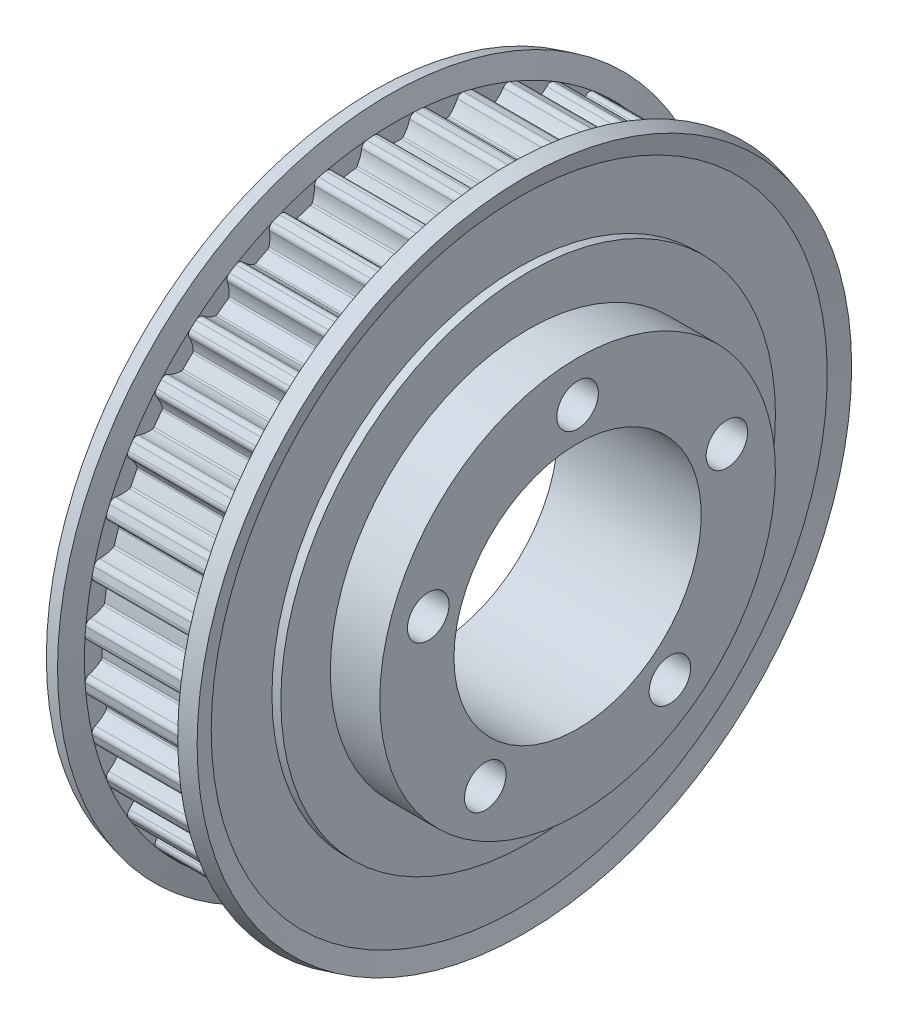
SolidWorks part; units mm, degrees
ref_plane "Front Plane" through (0, 0, 0) normal (0, 0, 1) x (1, 0, 0)
ref_plane "Top Plane" through (0, 0, 0) normal (0, 1, 0) x (1, 0, 0)
ref_plane "Right Plane" through (0, 0, 0) normal (1, 0, 0) x (0, 0, -1)
ref_plane "Plane1" through (0, 0, 0) normal (0, 0, 1) x (1, 0, 0)
sketch "Sketch1" plane through (0, 0, 0) normal (0, 0, 1) x (1, 0, 0)
  line L0 (0, 0) -> (0, 25)
  line L1 (0, 25) -> (0.9, 25)
  line L2 (0.9, 25) -> (0.9, 31.1394)
  line L3 (0.9, 31.1394) -> (0.3784, 33.0859)
  line L4 (0.3784, 33.0859) -> (1.9239, 33.5)
  line L5 (1.9239, 33.5) -> (2.5, 31.35)
  line L6 (2.5, 31.35) -> (13.5, 31.35)
  line L7 (13.5, 31.35) -> (14.0761, 33.5)
  line L8 (14.0761, 33.5) -> (15.6216, 33.0859)
  line L9 (15.6216, 33.0859) -> (15.1, 31.1394)
  line L10 (15.1, 31.1394) -> (15.1, 25)
  line L11 (15.1, 25) -> (16, 25)
  line L12 (16, 25) -> (16, 23.5)
  line L13 (16, 23.5) -> (21, 23.5)
  line L14 (21, 23.5) -> (21, 0)
  line L15 (21, 0) -> (0, 0)
  line L16 (21, 0) -> (0, 0) construction
revolve "Revolve1" add sketch "Sketch1" angle 360 about L16
ref_plane "Plane2" through (0, 0, 0) normal (0, 0, 1) x (1, 0, 0)
sketch "Sketch2" plane through (0, 0, 0) normal (0, 0, 1) x (1, 0, 0)
  line L0 (0, 0) -> (0, 12.5)
  line L1 (0, 12.5) -> (21, 12.5)
  line L2 (21, 12.5) -> (21, 0)
  line L3 (21, 0) -> (0, 0)
  line L4 (21, 0) -> (0, 0) construction
revolve "Cut-Revolve1" cut sketch "Sketch2" angle 360 about L4
ref_plane "Plane3" through (2.5, 0, 0) normal (1, 0, 0) x (0, 0, -1)
sketch "Sketch3" plane through (2.5, 0, 0) normal (1, 0, 0) x (0, 0, -1)
  line L0 (2.0877, 31.2804) -> (2.0877, 31.7615)
  line L1 (-2.0877, 31.7615) -> (-2.0877, 31.2804)
  arc A0 (-2.0877, 31.2804) -> (-1.5225, 30.8836) centre (-2.0511, 30.7316) cw
  arc A1 (-1.5225, 30.8836) -> (-0.8639, 29.6599) centre (1.625, 31.7885) ccw
  arc A2 (-0.8639, 29.6599) -> (-0.6683, 29.5725) centre (-0.6739, 29.8224) ccw
  arc A3 (-0.6683, 29.5725) -> (0.6683, 29.5725) centre (0, 0) cw
  arc A4 (0.6683, 29.5725) -> (0.8639, 29.6599) centre (0.6739, 29.8224) ccw
  arc A5 (0.8639, 29.6599) -> (1.5225, 30.8836) centre (-1.625, 31.7885) ccw
  arc A6 (1.5225, 30.8836) -> (2.0877, 31.2804) centre (2.0511, 30.7316) cw
  arc A7 (2.0877, 31.7615) -> (-2.0877, 31.7615) centre (0, 0) ccw
extrude "Cut-Extrude1" cut sketch "Sketch3" along normal blind 11
ref_plane "Plane4" through (2.5, 0, 0) normal (1, 0, 0) x (0, 0, -1)
sketch "Sketch4" plane through (2.5, 0, 0) normal (1, 0, 0) x (0, 0, -1)
  line L0 (6.9554, 30.5687) -> (7.0306, 31.0438)
  line L1 (2.9066, 31.697) -> (2.8313, 31.2219)
  arc A0 (2.8313, 31.2219) -> (3.3275, 30.7415) centre (2.7816, 30.6741) cw
  arc A1 (3.3275, 30.7415) -> (3.7865, 29.4299) centre (6.5778, 31.1429) ccw
  arc A2 (3.7865, 29.4299) -> (3.9661, 29.3129) centre (3.9996, 29.5606) ccw
  arc A3 (3.9661, 29.3129) -> (5.2862, 29.1038) centre (0, 0) cw
  arc A4 (5.2862, 29.1038) -> (5.4931, 29.1596) centre (5.3309, 29.3498) ccw
  arc A5 (5.4931, 29.1596) -> (6.335, 30.2652) centre (3.3678, 31.6513) ccw
  arc A6 (6.335, 30.2652) -> (6.9554, 30.5687) centre (6.8333, 30.0324) cw
  arc A7 (7.0306, 31.0438) -> (2.9066, 31.697) centre (0, 0) ccw
extrude "Cut-Extrude2" cut sketch "Sketch4" along normal blind 11
ref_plane "Plane5" through (2.5, 0, 0) normal (1, 0, 0) x (0, 0, -1)
sketch "Sketch5" plane through (2.5, 0, 0) normal (1, 0, 0) x (0, 0, -1)
  line L0 (11.6517, 29.1043) -> (11.8004, 29.5618)
  line L1 (7.8293, 30.8521) -> (7.6806, 30.3946)
  arc A0 (7.6806, 30.3946) -> (8.0956, 29.8425) centre (7.5459, 29.8613) cw
  arc A1 (8.0956, 29.8425) -> (8.3438, 28.4752) centre (11.3687, 29.7305) ccw
  arc A2 (8.3438, 28.4752) -> (8.5028, 28.3316) centre (8.5747, 28.571) ccw
  arc A3 (8.5028, 28.3316) -> (9.774, 27.9186) centre (0, 0) cw
  arc A4 (9.774, 27.9186) -> (9.987, 27.9413) centre (9.8566, 28.1545) ccw
  arc A5 (9.987, 27.9413) -> (10.9915, 28.9016) centre (8.2777, 30.7348) ccw
  arc A6 (10.9915, 28.9016) -> (11.6517, 29.1043) centre (11.4473, 28.5937) cw
  arc A7 (11.8004, 29.5618) -> (7.8293, 30.8521) centre (0, 0) ccw
extrude "Cut-Extrude3" cut sketch "Sketch5" along normal blind 11
ref_plane "Plane6" through (2.5, 0, 0) normal (1, 0, 0) x (0, 0, -1)
sketch "Sketch6" plane through (2.5, 0, 0) normal (1, 0, 0) x (0, 0, -1)
  line L0 (16.0612, 26.9232) -> (16.2796, 27.3519)
  line L1 (12.5592, 29.2475) -> (12.3408, 28.8189)
  arc A0 (12.3408, 28.8189) -> (12.6643, 28.2087) centre (12.1243, 28.3133) cw
  arc A1 (12.6643, 28.2087) -> (12.6956, 26.8194) centre (15.8796, 27.586) ccw
  arc A2 (12.6956, 26.8194) -> (12.8302, 26.6526) centre (12.9386, 26.8779) ccw
  arc A3 (12.8302, 26.6526) -> (14.021, 26.0459) centre (0, 0) cw
  arc A4 (14.021, 26.0459) -> (14.2351, 26.035) centre (14.1396, 26.266) ccw
  arc A5 (14.2351, 26.035) -> (15.3774, 26.8263) centre (12.9838, 29.0615) ccw
  arc A6 (15.3774, 26.8263) -> (16.0612, 26.9232) centre (15.7794, 26.4509) cw
  arc A7 (16.2796, 27.3519) -> (12.5592, 29.2475) centre (0, 0) ccw
extrude "Cut-Extrude4" cut sketch "Sketch6" along normal blind 11
ref_plane "Plane7" through (2.5, 0, 0) normal (1, 0, 0) x (0, 0, -1)
sketch "Sketch7" plane through (2.5, 0, 0) normal (1, 0, 0) x (0, 0, -1)
  line L0 (20.0752, 24.0793) -> (20.3579, 24.4684)
  line L1 (16.9799, 26.9227) -> (16.6972, 26.5335)
  arc A0 (16.6972, 26.5335) -> (16.9212, 25.8803) centre (16.4042, 26.068) cw
  arc A1 (16.9212, 25.8803) -> (16.7347, 24.5032) centre (19.9995, 24.7623) ccw
  arc A2 (16.7347, 24.5032) -> (16.8416, 24.3174) centre (16.9839, 24.5229) ccw
  arc A3 (16.8416, 24.3174) -> (17.9229, 23.5318) centre (0, 0) cw
  arc A4 (17.9229, 23.5318) -> (18.1326, 23.4876) centre (18.0744, 23.7307) ccw
  arc A5 (18.1326, 23.4876) -> (19.3847, 24.0904) centre (17.3702, 26.6726) ccw
  arc A6 (19.3847, 24.0904) -> (20.0752, 24.0793) centre (19.723, 23.6568) cw
  arc A7 (20.3579, 24.4684) -> (16.9799, 26.9227) centre (0, 0) ccw
extrude "Cut-Extrude5" cut sketch "Sketch7" along normal blind 11
ref_plane "Plane8" through (2.5, 0, 0) normal (1, 0, 0) x (0, 0, -1)
sketch "Sketch8" plane through (2.5, 0, 0) normal (1, 0, 0) x (0, 0, -1)
  line L0 (23.5948, 20.6423) -> (23.935, 20.9825)
  line L1 (20.9825, 23.935) -> (20.6423, 23.5948)
  arc A0 (20.6423, 23.5948) -> (20.7614, 22.9146) centre (20.2802, 23.1809) cw
  arc A1 (20.7614, 22.9146) -> (20.3618, 21.5836) centre (23.6269, 21.3288) ccw
  arc A2 (20.3618, 21.5836) -> (20.4383, 21.3834) centre (20.6111, 21.5641) ccw
  arc A3 (20.4383, 21.3834) -> (21.3834, 20.4383) centre (0, 0) cw
  arc A4 (21.3834, 20.4383) -> (21.5836, 20.3618) centre (21.5641, 20.6111) ccw
  arc A5 (21.5836, 20.3618) -> (22.9146, 20.7614) centre (21.3288, 23.6269) ccw
  arc A6 (22.9146, 20.7614) -> (23.5948, 20.6423) centre (23.1809, 20.2802) cw
  arc A7 (23.935, 20.9825) -> (20.9825, 23.935) centre (0, 0) ccw
extrude "Cut-Extrude6" cut sketch "Sketch8" along normal blind 11
ref_plane "Plane9" through (2.5, 0, 0) normal (1, 0, 0) x (0, 0, -1)
sketch "Sketch9" plane through (2.5, 0, 0) normal (1, 0, 0) x (0, 0, -1)
  line L0 (26.5335, 16.6972) -> (26.9227, 16.9799)
  line L1 (24.4684, 20.3579) -> (24.0793, 20.0752)
  arc A0 (24.0793, 20.0752) -> (24.0904, 19.3847) centre (23.6568, 19.723) cw
  arc A1 (24.0904, 19.3847) -> (23.4876, 18.1326) centre (26.6726, 17.3702) ccw
  arc A2 (23.4876, 18.1326) -> (23.5318, 17.9229) centre (23.7307, 18.0744) ccw
  arc A3 (23.5318, 17.9229) -> (24.3174, 16.8416) centre (0, 0) cw
  arc A4 (24.3174, 16.8416) -> (24.5032, 16.7347) centre (24.5229, 16.9839) ccw
  arc A5 (24.5032, 16.7347) -> (25.8803, 16.9212) centre (24.7623, 19.9995) ccw
  arc A6 (25.8803, 16.9212) -> (26.5335, 16.6972) centre (26.068, 16.4042) cw
  arc A7 (26.9227, 16.9799) -> (24.4684, 20.3579) centre (0, 0) ccw
extrude "Cut-Extrude7" cut sketch "Sketch9" along normal blind 11
ref_plane "Plane10" through (2.5, 0, 0) normal (1, 0, 0) x (0, 0, -1)
sketch "Sketch10" plane through (2.5, 0, 0) normal (1, 0, 0) x (0, 0, -1)
  line L0 (28.8189, 12.3408) -> (29.2475, 12.5592)
  line L1 (27.3519, 16.2796) -> (26.9232, 16.0612)
  arc A0 (26.9232, 16.0612) -> (26.8263, 15.3774) centre (26.4509, 15.7794) cw
  arc A1 (26.8263, 15.3774) -> (26.035, 14.2351) centre (29.0615, 12.9838) ccw
  arc A2 (26.035, 14.2351) -> (26.0459, 14.021) centre (26.266, 14.1396) ccw
  arc A3 (26.0459, 14.021) -> (26.6526, 12.8302) centre (0, 0) cw
  arc A4 (26.6526, 12.8302) -> (26.8194, 12.6956) centre (26.8779, 12.9386) ccw
  arc A5 (26.8194, 12.6956) -> (28.2087, 12.6643) centre (27.586, 15.8796) ccw
  arc A6 (28.2087, 12.6643) -> (28.8189, 12.3408) centre (28.3133, 12.1243) cw
  arc A7 (29.2475, 12.5592) -> (27.3519, 16.2796) centre (0, 0) ccw
extrude "Cut-Extrude8" cut sketch "Sketch10" along normal blind 11
ref_plane "Plane11" through (2.5, 0, 0) normal (1, 0, 0) x (0, 0, -1)
sketch "Sketch11" plane through (2.5, 0, 0) normal (1, 0, 0) x (0, 0, -1)
  line L0 (30.3946, 7.6806) -> (30.8521, 7.8293)
  line L1 (29.5618, 11.8004) -> (29.1043, 11.6517)
  arc A0 (29.1043, 11.6517) -> (28.9016, 10.9915) centre (28.5937, 11.4473) cw
  arc A1 (28.9016, 10.9915) -> (27.9413, 9.987) centre (30.7348, 8.2777) ccw
  arc A2 (27.9413, 9.987) -> (27.9186, 9.774) centre (28.1545, 9.8566) ccw
  arc A3 (27.9186, 9.774) -> (28.3316, 8.5028) centre (0, 0) cw
  arc A4 (28.3316, 8.5028) -> (28.4752, 8.3438) centre (28.571, 8.5747) ccw
  arc A5 (28.4752, 8.3438) -> (29.8425, 8.0956) centre (29.7305, 11.3687) ccw
  arc A6 (29.8425, 8.0956) -> (30.3946, 7.6806) centre (29.8613, 7.5459) cw
  arc A7 (30.8521, 7.8293) -> (29.5618, 11.8004) centre (0, 0) ccw
extrude "Cut-Extrude9" cut sketch "Sketch11" along normal blind 11
ref_plane "Plane12" through (2.5, 0, 0) normal (1, 0, 0) x (0, 0, -1)
sketch "Sketch12" plane through (2.5, 0, 0) normal (1, 0, 0) x (0, 0, -1)
  line L0 (31.2219, 2.8313) -> (31.697, 2.9066)
  line L1 (31.0438, 7.0306) -> (30.5687, 6.9554)
  arc A0 (30.5687, 6.9554) -> (30.2652, 6.335) centre (30.0324, 6.8333) cw
  arc A1 (30.2652, 6.335) -> (29.1596, 5.4931) centre (31.6513, 3.3678) ccw
  arc A2 (29.1596, 5.4931) -> (29.1038, 5.2862) centre (29.3498, 5.3309) ccw
  arc A3 (29.1038, 5.2862) -> (29.3129, 3.9661) centre (0, 0) cw
  arc A4 (29.3129, 3.9661) -> (29.4299, 3.7865) centre (29.5606, 3.9996) ccw
  arc A5 (29.4299, 3.7865) -> (30.7415, 3.3275) centre (31.1429, 6.5778) ccw
  arc A6 (30.7415, 3.3275) -> (31.2219, 2.8313) centre (30.6741, 2.7816) cw
  arc A7 (31.697, 2.9066) -> (31.0438, 7.0306) centre (0, 0) ccw
extrude "Cut-Extrude10" cut sketch "Sketch12" along normal blind 11
ref_plane "Plane13" through (2.5, 0, 0) normal (1, 0, 0) x (0, 0, -1)
sketch "Sketch13" plane through (2.5, 0, 0) normal (1, 0, 0) x (0, 0, -1)
  line L0 (31.2804, -2.0877) -> (31.7615, -2.0877)
  line L1 (31.7615, 2.0877) -> (31.2804, 2.0877)
  arc A0 (31.2804, 2.0877) -> (30.8836, 1.5225) centre (30.7316, 2.0511) cw
  arc A1 (30.8836, 1.5225) -> (29.6599, 0.8639) centre (31.7885, -1.625) ccw
  arc A2 (29.6599, 0.8639) -> (29.5725, 0.6683) centre (29.8224, 0.6739) ccw
  arc A3 (29.5725, 0.6683) -> (29.5725, -0.6683) centre (0, 0) cw
  arc A4 (29.5725, -0.6683) -> (29.6599, -0.8639) centre (29.8224, -0.6739) ccw
  arc A5 (29.6599, -0.8639) -> (30.8836, -1.5225) centre (31.7885, 1.625) ccw
  arc A6 (30.8836, -1.5225) -> (31.2804, -2.0877) centre (30.7316, -2.0511) cw
  arc A7 (31.7615, -2.0877) -> (31.7615, 2.0877) centre (0, 0) ccw
extrude "Cut-Extrude11" cut sketch "Sketch13" along normal blind 11
ref_plane "Plane14" through (2.5, 0, 0) normal (1, 0, 0) x (0, 0, -1)
sketch "Sketch14" plane through (2.5, 0, 0) normal (1, 0, 0) x (0, 0, -1)
  line L0 (30.5687, -6.9554) -> (31.0438, -7.0306)
  line L1 (31.697, -2.9066) -> (31.2219, -2.8313)
  arc A0 (31.2219, -2.8313) -> (30.7415, -3.3275) centre (30.6741, -2.7816) cw
  arc A1 (30.7415, -3.3275) -> (29.4299, -3.7865) centre (31.1429, -6.5778) ccw
  arc A2 (29.4299, -3.7865) -> (29.3129, -3.9661) centre (29.5606, -3.9996) ccw
  arc A3 (29.3129, -3.9661) -> (29.1038, -5.2862) centre (0, 0) cw
  arc A4 (29.1038, -5.2862) -> (29.1596, -5.4931) centre (29.3498, -5.3309) ccw
  arc A5 (29.1596, -5.4931) -> (30.2652, -6.335) centre (31.6513, -3.3678) ccw
  arc A6 (30.2652, -6.335) -> (30.5687, -6.9554) centre (30.0324, -6.8333) cw
  arc A7 (31.0438, -7.0306) -> (31.697, -2.9066) centre (0, 0) ccw
extrude "Cut-Extrude12" cut sketch "Sketch14" along normal blind 11
ref_plane "Plane15" through (2.5, 0, 0) normal (1, 0, 0) x (0, 0, -1)
sketch "Sketch15" plane through (2.5, 0, 0) normal (1, 0, 0) x (0, 0, -1)
  line L0 (29.1043, -11.6517) -> (29.5618, -11.8004)
  line L1 (30.8521, -7.8293) -> (30.3946, -7.6806)
  arc A0 (30.3946, -7.6806) -> (29.8425, -8.0956) centre (29.8613, -7.5459) cw
  arc A1 (29.8425, -8.0956) -> (28.4752, -8.3438) centre (29.7305, -11.3687) ccw
  arc A2 (28.4752, -8.3438) -> (28.3316, -8.5028) centre (28.571, -8.5747) ccw
  arc A3 (28.3316, -8.5028) -> (27.9186, -9.774) centre (0, 0) cw
  arc A4 (27.9186, -9.774) -> (27.9413, -9.987) centre (28.1545, -9.8566) ccw
  arc A5 (27.9413, -9.987) -> (28.9016, -10.9915) centre (30.7348, -8.2777) ccw
  arc A6 (28.9016, -10.9915) -> (29.1043, -11.6517) centre (28.5937, -11.4473) cw
  arc A7 (29.5618, -11.8004) -> (30.8521, -7.8293) centre (0, 0) ccw
extrude "Cut-Extrude13" cut sketch "Sketch15" along normal blind 11
ref_plane "Plane16" through (2.5, 0, 0) normal (1, 0, 0) x (0, 0, -1)
sketch "Sketch16" plane through (2.5, 0, 0) normal (1, 0, 0) x (0, 0, -1)
  line L0 (26.9232, -16.0612) -> (27.3519, -16.2796)
  line L1 (29.2475, -12.5592) -> (28.8189, -12.3408)
  arc A0 (28.8189, -12.3408) -> (28.2087, -12.6643) centre (28.3133, -12.1243) cw
  arc A1 (28.2087, -12.6643) -> (26.8194, -12.6956) centre (27.586, -15.8796) ccw
  arc A2 (26.8194, -12.6956) -> (26.6526, -12.8302) centre (26.8779, -12.9386) ccw
  arc A3 (26.6526, -12.8302) -> (26.0459, -14.021) centre (0, 0) cw
  arc A4 (26.0459, -14.021) -> (26.035, -14.2351) centre (26.266, -14.1396) ccw
  arc A5 (26.035, -14.2351) -> (26.8263, -15.3774) centre (29.0615, -12.9838) ccw
  arc A6 (26.8263, -15.3774) -> (26.9232, -16.0612) centre (26.4509, -15.7794) cw
  arc A7 (27.3519, -16.2796) -> (29.2475, -12.5592) centre (0, 0) ccw
extrude "Cut-Extrude14" cut sketch "Sketch16" along normal blind 11
ref_plane "Plane17" through (2.5, 0, 0) normal (1, 0, 0) x (0, 0, -1)
sketch "Sketch17" plane through (2.5, 0, 0) normal (1, 0, 0) x (0, 0, -1)
  line L0 (24.0793, -20.0752) -> (24.4684, -20.3579)
  line L1 (26.9227, -16.9799) -> (26.5335, -16.6972)
  arc A0 (26.5335, -16.6972) -> (25.8803, -16.9212) centre (26.068, -16.4042) cw
  arc A1 (25.8803, -16.9212) -> (24.5032, -16.7347) centre (24.7623, -19.9995) ccw
  arc A2 (24.5032, -16.7347) -> (24.3174, -16.8416) centre (24.5229, -16.9839) ccw
  arc A3 (24.3174, -16.8416) -> (23.5318, -17.9229) centre (0, 0) cw
  arc A4 (23.5318, -17.9229) -> (23.4876, -18.1326) centre (23.7307, -18.0744) ccw
  arc A5 (23.4876, -18.1326) -> (24.0904, -19.3847) centre (26.6726, -17.3702) ccw
  arc A6 (24.0904, -19.3847) -> (24.0793, -20.0752) centre (23.6568, -19.723) cw
  arc A7 (24.4684, -20.3579) -> (26.9227, -16.9799) centre (0, 0) ccw
extrude "Cut-Extrude15" cut sketch "Sketch17" along normal blind 11
ref_plane "Plane18" through (2.5, 0, 0) normal (1, 0, 0) x (0, 0, -1)
sketch "Sketch18" plane through (2.5, 0, 0) normal (1, 0, 0) x (0, 0, -1)
  line L0 (20.6423, -23.5948) -> (20.9825, -23.935)
  line L1 (23.935, -20.9825) -> (23.5948, -20.6423)
  arc A0 (23.5948, -20.6423) -> (22.9146, -20.7614) centre (23.1809, -20.2802) cw
  arc A1 (22.9146, -20.7614) -> (21.5836, -20.3618) centre (21.3288, -23.6269) ccw
  arc A2 (21.5836, -20.3618) -> (21.3834, -20.4383) centre (21.5641, -20.6111) ccw
  arc A3 (21.3834, -20.4383) -> (20.4383, -21.3834) centre (0, 0) cw
  arc A4 (20.4383, -21.3834) -> (20.3618, -21.5836) centre (20.6111, -21.5641) ccw
  arc A5 (20.3618, -21.5836) -> (20.7614, -22.9146) centre (23.6269, -21.3288) ccw
  arc A6 (20.7614, -22.9146) -> (20.6423, -23.5948) centre (20.2802, -23.1809) cw
  arc A7 (20.9825, -23.935) -> (23.935, -20.9825) centre (0, 0) ccw
extrude "Cut-Extrude16" cut sketch "Sketch18" along normal blind 11
ref_plane "Plane19" through (2.5, 0, 0) normal (1, 0, 0) x (0, 0, -1)
sketch "Sketch19" plane through (2.5, 0, 0) normal (1, 0, 0) x (0, 0, -1)
  line L0 (16.6972, -26.5335) -> (16.9799, -26.9227)
  line L1 (20.3579, -24.4684) -> (20.0752, -24.0793)
  arc A0 (20.0752, -24.0793) -> (19.3847, -24.0904) centre (19.723, -23.6568) cw
  arc A1 (19.3847, -24.0904) -> (18.1326, -23.4876) centre (17.3702, -26.6726) ccw
  arc A2 (18.1326, -23.4876) -> (17.9229, -23.5318) centre (18.0744, -23.7307) ccw
  arc A3 (17.9229, -23.5318) -> (16.8416, -24.3174) centre (0, 0) cw
  arc A4 (16.8416, -24.3174) -> (16.7347, -24.5032) centre (16.9839, -24.5229) ccw
  arc A5 (16.7347, -24.5032) -> (16.9212, -25.8803) centre (19.9995, -24.7623) ccw
  arc A6 (16.9212, -25.8803) -> (16.6972, -26.5335) centre (16.4042, -26.068) cw
  arc A7 (16.9799, -26.9227) -> (20.3579, -24.4684) centre (0, 0) ccw
extrude "Cut-Extrude17" cut sketch "Sketch19" along normal blind 11
ref_plane "Plane20" through (2.5, 0, 0) normal (1, 0, 0) x (0, 0, -1)
sketch "Sketch20" plane through (2.5, 0, 0) normal (1, 0, 0) x (0, 0, -1)
  line L0 (12.3408, -28.8189) -> (12.5592, -29.2475)
  line L1 (16.2796, -27.3519) -> (16.0612, -26.9232)
  arc A0 (16.0612, -26.9232) -> (15.3774, -26.8263) centre (15.7794, -26.4509) cw
  arc A1 (15.3774, -26.8263) -> (14.2351, -26.035) centre (12.9838, -29.0615) ccw
  arc A2 (14.2351, -26.035) -> (14.021, -26.0459) centre (14.1396, -26.266) ccw
  arc A3 (14.021, -26.0459) -> (12.8302, -26.6526) centre (0, 0) cw
  arc A4 (12.8302, -26.6526) -> (12.6956, -26.8194) centre (12.9386, -26.8779) ccw
  arc A5 (12.6956, -26.8194) -> (12.6643, -28.2087) centre (15.8796, -27.586) ccw
  arc A6 (12.6643, -28.2087) -> (12.3408, -28.8189) centre (12.1243, -28.3133) cw
  arc A7 (12.5592, -29.2475) -> (16.2796, -27.3519) centre (0, 0) ccw
extrude "Cut-Extrude18" cut sketch "Sketch20" along normal blind 11
ref_plane "Plane21" through (2.5, 0, 0) normal (1, 0, 0) x (0, 0, -1)
sketch "Sketch21" plane through (2.5, 0, 0) normal (1, 0, 0) x (0, 0, -1)
  line L0 (7.6806, -30.3946) -> (7.8293, -30.8521)
  line L1 (11.8004, -29.5618) -> (11.6517, -29.1043)
  arc A0 (11.6517, -29.1043) -> (10.9915, -28.9016) centre (11.4473, -28.5937) cw
  arc A1 (10.9915, -28.9016) -> (9.987, -27.9413) centre (8.2777, -30.7348) ccw
  arc A2 (9.987, -27.9413) -> (9.774, -27.9186) centre (9.8566, -28.1545) ccw
  arc A3 (9.774, -27.9186) -> (8.5028, -28.3316) centre (0, 0) cw
  arc A4 (8.5028, -28.3316) -> (8.3438, -28.4752) centre (8.5747, -28.571) ccw
  arc A5 (8.3438, -28.4752) -> (8.0956, -29.8425) centre (11.3687, -29.7305) ccw
  arc A6 (8.0956, -29.8425) -> (7.6806, -30.3946) centre (7.5459, -29.8613) cw
  arc A7 (7.8293, -30.8521) -> (11.8004, -29.5618) centre (0, 0) ccw
extrude "Cut-Extrude19" cut sketch "Sketch21" along normal blind 11
ref_plane "Plane22" through (2.5, 0, 0) normal (1, 0, 0) x (0, 0, -1)
sketch "Sketch22" plane through (2.5, 0, 0) normal (1, 0, 0) x (0, 0, -1)
  line L0 (2.8313, -31.2219) -> (2.9066, -31.697)
  line L1 (7.0306, -31.0438) -> (6.9554, -30.5687)
  arc A0 (6.9554, -30.5687) -> (6.335, -30.2652) centre (6.8333, -30.0324) cw
  arc A1 (6.335, -30.2652) -> (5.4931, -29.1596) centre (3.3678, -31.6513) ccw
  arc A2 (5.4931, -29.1596) -> (5.2862, -29.1038) centre (5.3309, -29.3498) ccw
  arc A3 (5.2862, -29.1038) -> (3.9661, -29.3129) centre (0, 0) cw
  arc A4 (3.9661, -29.3129) -> (3.7865, -29.4299) centre (3.9996, -29.5606) ccw
  arc A5 (3.7865, -29.4299) -> (3.3275, -30.7415) centre (6.5778, -31.1429) ccw
  arc A6 (3.3275, -30.7415) -> (2.8313, -31.2219) centre (2.7816, -30.6741) cw
  arc A7 (2.9066, -31.697) -> (7.0306, -31.0438) centre (0, 0) ccw
extrude "Cut-Extrude20" cut sketch "Sketch22" along normal blind 11
ref_plane "Plane23" through (2.5, 0, 0) normal (1, 0, 0) x (0, 0, -1)
sketch "Sketch23" plane through (2.5, 0, 0) normal (1, 0, 0) x (0, 0, -1)
  line L0 (-2.0877, -31.2804) -> (-2.0877, -31.7615)
  line L1 (2.0877, -31.7615) -> (2.0877, -31.2804)
  arc A0 (2.0877, -31.2804) -> (1.5225, -30.8836) centre (2.0511, -30.7316) cw
  arc A1 (1.5225, -30.8836) -> (0.8639, -29.6599) centre (-1.625, -31.7885) ccw
  arc A2 (0.8639, -29.6599) -> (0.6683, -29.5725) centre (0.6739, -29.8224) ccw
  arc A3 (0.6683, -29.5725) -> (-0.6683, -29.5725) centre (0, 0) cw
  arc A4 (-0.6683, -29.5725) -> (-0.8639, -29.6599) centre (-0.6739, -29.8224) ccw
  arc A5 (-0.8639, -29.6599) -> (-1.5225, -30.8836) centre (1.625, -31.7885) ccw
  arc A6 (-1.5225, -30.8836) -> (-2.0877, -31.2804) centre (-2.0511, -30.7316) cw
  arc A7 (-2.0877, -31.7615) -> (2.0877, -31.7615) centre (0, 0) ccw
extrude "Cut-Extrude21" cut sketch "Sketch23" along normal blind 11
ref_plane "Plane24" through (2.5, 0, 0) normal (1, 0, 0) x (0, 0, -1)
sketch "Sketch24" plane through (2.5, 0, 0) normal (1, 0, 0) x (0, 0, -1)
  line L0 (-6.9554, -30.5687) -> (-7.0306, -31.0438)
  line L1 (-2.9066, -31.697) -> (-2.8313, -31.2219)
  arc A0 (-2.8313, -31.2219) -> (-3.3275, -30.7415) centre (-2.7816, -30.6741) cw
  arc A1 (-3.3275, -30.7415) -> (-3.7865, -29.4299) centre (-6.5778, -31.1429) ccw
  arc A2 (-3.7865, -29.4299) -> (-3.9661, -29.3129) centre (-3.9996, -29.5606) ccw
  arc A3 (-3.9661, -29.3129) -> (-5.2862, -29.1038) centre (0, 0) cw
  arc A4 (-5.2862, -29.1038) -> (-5.4931, -29.1596) centre (-5.3309, -29.3498) ccw
  arc A5 (-5.4931, -29.1596) -> (-6.335, -30.2652) centre (-3.3678, -31.6513) ccw
  arc A6 (-6.335, -30.2652) -> (-6.9554, -30.5687) centre (-6.8333, -30.0324) cw
  arc A7 (-7.0306, -31.0438) -> (-2.9066, -31.697) centre (0, 0) ccw
extrude "Cut-Extrude22" cut sketch "Sketch24" along normal blind 11
ref_plane "Plane25" through (2.5, 0, 0) normal (1, 0, 0) x (0, 0, -1)
sketch "Sketch25" plane through (2.5, 0, 0) normal (1, 0, 0) x (0, 0, -1)
  line L0 (-11.6517, -29.1043) -> (-11.8004, -29.5618)
  line L1 (-7.8293, -30.8521) -> (-7.6806, -30.3946)
  arc A0 (-7.6806, -30.3946) -> (-8.0956, -29.8425) centre (-7.5459, -29.8613) cw
  arc A1 (-8.0956, -29.8425) -> (-8.3438, -28.4752) centre (-11.3687, -29.7305) ccw
  arc A2 (-8.3438, -28.4752) -> (-8.5028, -28.3316) centre (-8.5747, -28.571) ccw
  arc A3 (-8.5028, -28.3316) -> (-9.774, -27.9186) centre (0, 0) cw
  arc A4 (-9.774, -27.9186) -> (-9.987, -27.9413) centre (-9.8566, -28.1545) ccw
  arc A5 (-9.987, -27.9413) -> (-10.9915, -28.9016) centre (-8.2777, -30.7348) ccw
  arc A6 (-10.9915, -28.9016) -> (-11.6517, -29.1043) centre (-11.4473, -28.5937) cw
  arc A7 (-11.8004, -29.5618) -> (-7.8293, -30.8521) centre (0, 0) ccw
extrude "Cut-Extrude23" cut sketch "Sketch25" along normal blind 11
ref_plane "Plane26" through (2.5, 0, 0) normal (1, 0, 0) x (0, 0, -1)
sketch "Sketch26" plane through (2.5, 0, 0) normal (1, 0, 0) x (0, 0, -1)
  line L0 (-16.0612, -26.9232) -> (-16.2796, -27.3519)
  line L1 (-12.5592, -29.2475) -> (-12.3408, -28.8189)
  arc A0 (-12.3408, -28.8189) -> (-12.6643, -28.2087) centre (-12.1243, -28.3133) cw
  arc A1 (-12.6643, -28.2087) -> (-12.6956, -26.8194) centre (-15.8796, -27.586) ccw
  arc A2 (-12.6956, -26.8194) -> (-12.8302, -26.6526) centre (-12.9386, -26.8779) ccw
  arc A3 (-12.8302, -26.6526) -> (-14.021, -26.0459) centre (0, 0) cw
  arc A4 (-14.021, -26.0459) -> (-14.2351, -26.035) centre (-14.1396, -26.266) ccw
  arc A5 (-14.2351, -26.035) -> (-15.3774, -26.8263) centre (-12.9838, -29.0615) ccw
  arc A6 (-15.3774, -26.8263) -> (-16.0612, -26.9232) centre (-15.7794, -26.4509) cw
  arc A7 (-16.2796, -27.3519) -> (-12.5592, -29.2475) centre (0, 0) ccw
extrude "Cut-Extrude24" cut sketch "Sketch26" along normal blind 11
ref_plane "Plane27" through (2.5, 0, 0) normal (1, 0, 0) x (0, 0, -1)
sketch "Sketch27" plane through (2.5, 0, 0) normal (1, 0, 0) x (0, 0, -1)
  line L0 (-20.0752, -24.0793) -> (-20.3579, -24.4684)
  line L1 (-16.9799, -26.9227) -> (-16.6972, -26.5335)
  arc A0 (-16.6972, -26.5335) -> (-16.9212, -25.8803) centre (-16.4042, -26.068) cw
  arc A1 (-16.9212, -25.8803) -> (-16.7347, -24.5032) centre (-19.9995, -24.7623) ccw
  arc A2 (-16.7347, -24.5032) -> (-16.8416, -24.3174) centre (-16.9839, -24.5229) ccw
  arc A3 (-16.8416, -24.3174) -> (-17.9229, -23.5318) centre (0, 0) cw
  arc A4 (-17.9229, -23.5318) -> (-18.1326, -23.4876) centre (-18.0744, -23.7307) ccw
  arc A5 (-18.1326, -23.4876) -> (-19.3847, -24.0904) centre (-17.3702, -26.6726) ccw
  arc A6 (-19.3847, -24.0904) -> (-20.0752, -24.0793) centre (-19.723, -23.6568) cw
  arc A7 (-20.3579, -24.4684) -> (-16.9799, -26.9227) centre (0, 0) ccw
extrude "Cut-Extrude25" cut sketch "Sketch27" along normal blind 11
ref_plane "Plane28" through (2.5, 0, 0) normal (1, 0, 0) x (0, 0, -1)
sketch "Sketch28" plane through (2.5, 0, 0) normal (1, 0, 0) x (0, 0, -1)
  line L0 (-23.5948, -20.6423) -> (-23.935, -20.9825)
  line L1 (-20.9825, -23.935) -> (-20.6423, -23.5948)
  arc A0 (-20.6423, -23.5948) -> (-20.7614, -22.9146) centre (-20.2802, -23.1809) cw
  arc A1 (-20.7614, -22.9146) -> (-20.3618, -21.5836) centre (-23.6269, -21.3288) ccw
  arc A2 (-20.3618, -21.5836) -> (-20.4383, -21.3834) centre (-20.6111, -21.5641) ccw
  arc A3 (-20.4383, -21.3834) -> (-21.3834, -20.4383) centre (0, 0) cw
  arc A4 (-21.3834, -20.4383) -> (-21.5836, -20.3618) centre (-21.5641, -20.6111) ccw
  arc A5 (-21.5836, -20.3618) -> (-22.9146, -20.7614) centre (-21.3288, -23.6269) ccw
  arc A6 (-22.9146, -20.7614) -> (-23.5948, -20.6423) centre (-23.1809, -20.2802) cw
  arc A7 (-23.935, -20.9825) -> (-20.9825, -23.935) centre (0, 0) ccw
extrude "Cut-Extrude26" cut sketch "Sketch28" along normal blind 11
ref_plane "Plane29" through (2.5, 0, 0) normal (1, 0, 0) x (0, 0, -1)
sketch "Sketch29" plane through (2.5, 0, 0) normal (1, 0, 0) x (0, 0, -1)
  line L0 (-26.5335, -16.6972) -> (-26.9227, -16.9799)
  line L1 (-24.4684, -20.3579) -> (-24.0793, -20.0752)
  arc A0 (-24.0793, -20.0752) -> (-24.0904, -19.3847) centre (-23.6568, -19.723) cw
  arc A1 (-24.0904, -19.3847) -> (-23.4876, -18.1326) centre (-26.6726, -17.3702) ccw
  arc A2 (-23.4876, -18.1326) -> (-23.5318, -17.9229) centre (-23.7307, -18.0744) ccw
  arc A3 (-23.5318, -17.9229) -> (-24.3174, -16.8416) centre (0, 0) cw
  arc A4 (-24.3174, -16.8416) -> (-24.5032, -16.7347) centre (-24.5229, -16.9839) ccw
  arc A5 (-24.5032, -16.7347) -> (-25.8803, -16.9212) centre (-24.7623, -19.9995) ccw
  arc A6 (-25.8803, -16.9212) -> (-26.5335, -16.6972) centre (-26.068, -16.4042) cw
  arc A7 (-26.9227, -16.9799) -> (-24.4684, -20.3579) centre (0, 0) ccw
extrude "Cut-Extrude27" cut sketch "Sketch29" along normal blind 11
ref_plane "Plane30" through (2.5, 0, 0) normal (1, 0, 0) x (0, 0, -1)
sketch "Sketch30" plane through (2.5, 0, 0) normal (1, 0, 0) x (0, 0, -1)
  line L0 (-28.8189, -12.3408) -> (-29.2475, -12.5592)
  line L1 (-27.3519, -16.2796) -> (-26.9232, -16.0612)
  arc A0 (-26.9232, -16.0612) -> (-26.8263, -15.3774) centre (-26.4509, -15.7794) cw
  arc A1 (-26.8263, -15.3774) -> (-26.035, -14.2351) centre (-29.0615, -12.9838) ccw
  arc A2 (-26.035, -14.2351) -> (-26.0459, -14.021) centre (-26.266, -14.1396) ccw
  arc A3 (-26.0459, -14.021) -> (-26.6526, -12.8302) centre (0, 0) cw
  arc A4 (-26.6526, -12.8302) -> (-26.8194, -12.6956) centre (-26.8779, -12.9386) ccw
  arc A5 (-26.8194, -12.6956) -> (-28.2087, -12.6643) centre (-27.586, -15.8796) ccw
  arc A6 (-28.2087, -12.6643) -> (-28.8189, -12.3408) centre (-28.3133, -12.1243) cw
  arc A7 (-29.2475, -12.5592) -> (-27.3519, -16.2796) centre (0, 0) ccw
extrude "Cut-Extrude28" cut sketch "Sketch30" along normal blind 11
ref_plane "Plane31" through (2.5, 0, 0) normal (1, 0, 0) x (0, 0, -1)
sketch "Sketch31" plane through (2.5, 0, 0) normal (1, 0, 0) x (0, 0, -1)
  line L0 (-30.3946, -7.6806) -> (-30.8521, -7.8293)
  line L1 (-29.5618, -11.8004) -> (-29.1043, -11.6517)
  arc A0 (-29.1043, -11.6517) -> (-28.9016, -10.9915) centre (-28.5937, -11.4473) cw
  arc A1 (-28.9016, -10.9915) -> (-27.9413, -9.987) centre (-30.7348, -8.2777) ccw
  arc A2 (-27.9413, -9.987) -> (-27.9186, -9.774) centre (-28.1545, -9.8566) ccw
  arc A3 (-27.9186, -9.774) -> (-28.3316, -8.5028) centre (0, 0) cw
  arc A4 (-28.3316, -8.5028) -> (-28.4752, -8.3438) centre (-28.571, -8.5747) ccw
  arc A5 (-28.4752, -8.3438) -> (-29.8425, -8.0956) centre (-29.7305, -11.3687) ccw
  arc A6 (-29.8425, -8.0956) -> (-30.3946, -7.6806) centre (-29.8613, -7.5459) cw
  arc A7 (-30.8521, -7.8293) -> (-29.5618, -11.8004) centre (0, 0) ccw
extrude "Cut-Extrude29" cut sketch "Sketch31" along normal blind 11
ref_plane "Plane32" through (2.5, 0, 0) normal (1, 0, 0) x (0, 0, -1)
sketch "Sketch32" plane through (2.5, 0, 0) normal (1, 0, 0) x (0, 0, -1)
  line L0 (-31.2219, -2.8313) -> (-31.697, -2.9066)
  line L1 (-31.0438, -7.0306) -> (-30.5687, -6.9554)
  arc A0 (-30.5687, -6.9554) -> (-30.2652, -6.335) centre (-30.0324, -6.8333) cw
  arc A1 (-30.2652, -6.335) -> (-29.1596, -5.4931) centre (-31.6513, -3.3678) ccw
  arc A2 (-29.1596, -5.4931) -> (-29.1038, -5.2862) centre (-29.3498, -5.3309) ccw
  arc A3 (-29.1038, -5.2862) -> (-29.3129, -3.9661) centre (0, 0) cw
  arc A4 (-29.3129, -3.9661) -> (-29.4299, -3.7865) centre (-29.5606, -3.9996) ccw
  arc A5 (-29.4299, -3.7865) -> (-30.7415, -3.3275) centre (-31.1429, -6.5778) ccw
  arc A6 (-30.7415, -3.3275) -> (-31.2219, -2.8313) centre (-30.6741, -2.7816) cw
  arc A7 (-31.697, -2.9066) -> (-31.0438, -7.0306) centre (0, 0) ccw
extrude "Cut-Extrude30" cut sketch "Sketch32" along normal blind 11
ref_plane "Plane33" through (2.5, 0, 0) normal (1, 0, 0) x (0, 0, -1)
sketch "Sketch33" plane through (2.5, 0, 0) normal (1, 0, 0) x (0, 0, -1)
  line L0 (-31.2804, 2.0877) -> (-31.7615, 2.0877)
  line L1 (-31.7615, -2.0877) -> (-31.2804, -2.0877)
  arc A0 (-31.2804, -2.0877) -> (-30.8836, -1.5225) centre (-30.7316, -2.0511) cw
  arc A1 (-30.8836, -1.5225) -> (-29.6599, -0.8639) centre (-31.7885, 1.625) ccw
  arc A2 (-29.6599, -0.8639) -> (-29.5725, -0.6683) centre (-29.8224, -0.6739) ccw
  arc A3 (-29.5725, -0.6683) -> (-29.5725, 0.6683) centre (0, 0) cw
  arc A4 (-29.5725, 0.6683) -> (-29.6599, 0.8639) centre (-29.8224, 0.6739) ccw
  arc A5 (-29.6599, 0.8639) -> (-30.8836, 1.5225) centre (-31.7885, -1.625) ccw
  arc A6 (-30.8836, 1.5225) -> (-31.2804, 2.0877) centre (-30.7316, 2.0511) cw
  arc A7 (-31.7615, 2.0877) -> (-31.7615, -2.0877) centre (0, 0) ccw
extrude "Cut-Extrude31" cut sketch "Sketch33" along normal blind 11
ref_plane "Plane34" through (2.5, 0, 0) normal (1, 0, 0) x (0, 0, -1)
sketch "Sketch34" plane through (2.5, 0, 0) normal (1, 0, 0) x (0, 0, -1)
  line L0 (-30.5687, 6.9554) -> (-31.0438, 7.0306)
  line L1 (-31.697, 2.9066) -> (-31.2219, 2.8313)
  arc A0 (-31.2219, 2.8313) -> (-30.7415, 3.3275) centre (-30.6741, 2.7816) cw
  arc A1 (-30.7415, 3.3275) -> (-29.4299, 3.7865) centre (-31.1429, 6.5778) ccw
  arc A2 (-29.4299, 3.7865) -> (-29.3129, 3.9661) centre (-29.5606, 3.9996) ccw
  arc A3 (-29.3129, 3.9661) -> (-29.1038, 5.2862) centre (0, 0) cw
  arc A4 (-29.1038, 5.2862) -> (-29.1596, 5.4931) centre (-29.3498, 5.3309) ccw
  arc A5 (-29.1596, 5.4931) -> (-30.2652, 6.335) centre (-31.6513, 3.3678) ccw
  arc A6 (-30.2652, 6.335) -> (-30.5687, 6.9554) centre (-30.0324, 6.8333) cw
  arc A7 (-31.0438, 7.0306) -> (-31.697, 2.9066) centre (0, 0) ccw
extrude "Cut-Extrude32" cut sketch "Sketch34" along normal blind 11
ref_plane "Plane35" through (2.5, 0, 0) normal (1, 0, 0) x (0, 0, -1)
sketch "Sketch35" plane through (2.5, 0, 0) normal (1, 0, 0) x (0, 0, -1)
  line L0 (-29.1043, 11.6517) -> (-29.5618, 11.8004)
  line L1 (-30.8521, 7.8293) -> (-30.3946, 7.6806)
  arc A0 (-30.3946, 7.6806) -> (-29.8425, 8.0956) centre (-29.8613, 7.5459) cw
  arc A1 (-29.8425, 8.0956) -> (-28.4752, 8.3438) centre (-29.7305, 11.3687) ccw
  arc A2 (-28.4752, 8.3438) -> (-28.3316, 8.5028) centre (-28.571, 8.5747) ccw
  arc A3 (-28.3316, 8.5028) -> (-27.9186, 9.774) centre (0, 0) cw
  arc A4 (-27.9186, 9.774) -> (-27.9413, 9.987) centre (-28.1545, 9.8566) ccw
  arc A5 (-27.9413, 9.987) -> (-28.9016, 10.9915) centre (-30.7348, 8.2777) ccw
  arc A6 (-28.9016, 10.9915) -> (-29.1043, 11.6517) centre (-28.5937, 11.4473) cw
  arc A7 (-29.5618, 11.8004) -> (-30.8521, 7.8293) centre (0, 0) ccw
extrude "Cut-Extrude33" cut sketch "Sketch35" along normal blind 11
ref_plane "Plane36" through (2.5, 0, 0) normal (1, 0, 0) x (0, 0, -1)
sketch "Sketch36" plane through (2.5, 0, 0) normal (1, 0, 0) x (0, 0, -1)
  line L0 (-26.9232, 16.0612) -> (-27.3519, 16.2796)
  line L1 (-29.2475, 12.5592) -> (-28.8189, 12.3408)
  arc A0 (-28.8189, 12.3408) -> (-28.2087, 12.6643) centre (-28.3133, 12.1243) cw
  arc A1 (-28.2087, 12.6643) -> (-26.8194, 12.6956) centre (-27.586, 15.8796) ccw
  arc A2 (-26.8194, 12.6956) -> (-26.6526, 12.8302) centre (-26.8779, 12.9386) ccw
  arc A3 (-26.6526, 12.8302) -> (-26.0459, 14.021) centre (0, 0) cw
  arc A4 (-26.0459, 14.021) -> (-26.035, 14.2351) centre (-26.266, 14.1396) ccw
  arc A5 (-26.035, 14.2351) -> (-26.8263, 15.3774) centre (-29.0615, 12.9838) ccw
  arc A6 (-26.8263, 15.3774) -> (-26.9232, 16.0612) centre (-26.4509, 15.7794) cw
  arc A7 (-27.3519, 16.2796) -> (-29.2475, 12.5592) centre (0, 0) ccw
extrude "Cut-Extrude34" cut sketch "Sketch36" along normal blind 11
ref_plane "Plane37" through (2.5, 0, 0) normal (1, 0, 0) x (0, 0, -1)
sketch "Sketch37" plane through (2.5, 0, 0) normal (1, 0, 0) x (0, 0, -1)
  line L0 (-24.0793, 20.0752) -> (-24.4684, 20.3579)
  line L1 (-26.9227, 16.9799) -> (-26.5335, 16.6972)
  arc A0 (-26.5335, 16.6972) -> (-25.8803, 16.9212) centre (-26.068, 16.4042) cw
  arc A1 (-25.8803, 16.9212) -> (-24.5032, 16.7347) centre (-24.7623, 19.9995) ccw
  arc A2 (-24.5032, 16.7347) -> (-24.3174, 16.8416) centre (-24.5229, 16.9839) ccw
  arc A3 (-24.3174, 16.8416) -> (-23.5318, 17.9229) centre (0, 0) cw
  arc A4 (-23.5318, 17.9229) -> (-23.4876, 18.1326) centre (-23.7307, 18.0744) ccw
  arc A5 (-23.4876, 18.1326) -> (-24.0904, 19.3847) centre (-26.6726, 17.3702) ccw
  arc A6 (-24.0904, 19.3847) -> (-24.0793, 20.0752) centre (-23.6568, 19.723) cw
  arc A7 (-24.4684, 20.3579) -> (-26.9227, 16.9799) centre (0, 0) ccw
extrude "Cut-Extrude35" cut sketch "Sketch37" along normal blind 11
ref_plane "Plane38" through (2.5, 0, 0) normal (1, 0, 0) x (0, 0, -1)
sketch "Sketch38" plane through (2.5, 0, 0) normal (1, 0, 0) x (0, 0, -1)
  line L0 (-20.6423, 23.5948) -> (-20.9825, 23.935)
  line L1 (-23.935, 20.9825) -> (-23.5948, 20.6423)
  arc A0 (-23.5948, 20.6423) -> (-22.9146, 20.7614) centre (-23.1809, 20.2802) cw
  arc A1 (-22.9146, 20.7614) -> (-21.5836, 20.3618) centre (-21.3288, 23.6269) ccw
  arc A2 (-21.5836, 20.3618) -> (-21.3834, 20.4383) centre (-21.5641, 20.6111) ccw
  arc A3 (-21.3834, 20.4383) -> (-20.4383, 21.3834) centre (0, 0) cw
  arc A4 (-20.4383, 21.3834) -> (-20.3618, 21.5836) centre (-20.6111, 21.5641) ccw
  arc A5 (-20.3618, 21.5836) -> (-20.7614, 22.9146) centre (-23.6269, 21.3288) ccw
  arc A6 (-20.7614, 22.9146) -> (-20.6423, 23.5948) centre (-20.2802, 23.1809) cw
  arc A7 (-20.9825, 23.935) -> (-23.935, 20.9825) centre (0, 0) ccw
extrude "Cut-Extrude36" cut sketch "Sketch38" along normal blind 11
ref_plane "Plane39" through (2.5, 0, 0) normal (1, 0, 0) x (0, 0, -1)
sketch "Sketch39" plane through (2.5, 0, 0) normal (1, 0, 0) x (0, 0, -1)
  line L0 (-16.6972, 26.5335) -> (-16.9799, 26.9227)
  line L1 (-20.3579, 24.4684) -> (-20.0752, 24.0793)
  arc A0 (-20.0752, 24.0793) -> (-19.3847, 24.0904) centre (-19.723, 23.6568) cw
  arc A1 (-19.3847, 24.0904) -> (-18.1326, 23.4876) centre (-17.3702, 26.6726) ccw
  arc A2 (-18.1326, 23.4876) -> (-17.9229, 23.5318) centre (-18.0744, 23.7307) ccw
  arc A3 (-17.9229, 23.5318) -> (-16.8416, 24.3174) centre (0, 0) cw
  arc A4 (-16.8416, 24.3174) -> (-16.7347, 24.5032) centre (-16.9839, 24.5229) ccw
  arc A5 (-16.7347, 24.5032) -> (-16.9212, 25.8803) centre (-19.9995, 24.7623) ccw
  arc A6 (-16.9212, 25.8803) -> (-16.6972, 26.5335) centre (-16.4042, 26.068) cw
  arc A7 (-16.9799, 26.9227) -> (-20.3579, 24.4684) centre (0, 0) ccw
extrude "Cut-Extrude37" cut sketch "Sketch39" along normal blind 11
ref_plane "Plane40" through (2.5, 0, 0) normal (1, 0, 0) x (0, 0, -1)
sketch "Sketch40" plane through (2.5, 0, 0) normal (1, 0, 0) x (0, 0, -1)
  line L0 (-12.3408, 28.8189) -> (-12.5592, 29.2475)
  line L1 (-16.2796, 27.3519) -> (-16.0612, 26.9232)
  arc A0 (-16.0612, 26.9232) -> (-15.3774, 26.8263) centre (-15.7794, 26.4509) cw
  arc A1 (-15.3774, 26.8263) -> (-14.2351, 26.035) centre (-12.9838, 29.0615) ccw
  arc A2 (-14.2351, 26.035) -> (-14.021, 26.0459) centre (-14.1396, 26.266) ccw
  arc A3 (-14.021, 26.0459) -> (-12.8302, 26.6526) centre (0, 0) cw
  arc A4 (-12.8302, 26.6526) -> (-12.6956, 26.8194) centre (-12.9386, 26.8779) ccw
  arc A5 (-12.6956, 26.8194) -> (-12.6643, 28.2087) centre (-15.8796, 27.586) ccw
  arc A6 (-12.6643, 28.2087) -> (-12.3408, 28.8189) centre (-12.1243, 28.3133) cw
  arc A7 (-12.5592, 29.2475) -> (-16.2796, 27.3519) centre (0, 0) ccw
extrude "Cut-Extrude38" cut sketch "Sketch40" along normal blind 11
ref_plane "Plane41" through (2.5, 0, 0) normal (1, 0, 0) x (0, 0, -1)
sketch "Sketch41" plane through (2.5, 0, 0) normal (1, 0, 0) x (0, 0, -1)
  line L0 (-7.6806, 30.3946) -> (-7.8293, 30.8521)
  line L1 (-11.8004, 29.5618) -> (-11.6517, 29.1043)
  arc A0 (-11.6517, 29.1043) -> (-10.9915, 28.9016) centre (-11.4473, 28.5937) cw
  arc A1 (-10.9915, 28.9016) -> (-9.987, 27.9413) centre (-8.2777, 30.7348) ccw
  arc A2 (-9.987, 27.9413) -> (-9.774, 27.9186) centre (-9.8566, 28.1545) ccw
  arc A3 (-9.774, 27.9186) -> (-8.5028, 28.3316) centre (0, 0) cw
  arc A4 (-8.5028, 28.3316) -> (-8.3438, 28.4752) centre (-8.5747, 28.571) ccw
  arc A5 (-8.3438, 28.4752) -> (-8.0956, 29.8425) centre (-11.3687, 29.7305) ccw
  arc A6 (-8.0956, 29.8425) -> (-7.6806, 30.3946) centre (-7.5459, 29.8613) cw
  arc A7 (-7.8293, 30.8521) -> (-11.8004, 29.5618) centre (0, 0) ccw
extrude "Cut-Extrude39" cut sketch "Sketch41" along normal blind 11
ref_plane "Plane42" through (2.5, 0, 0) normal (1, 0, 0) x (0, 0, -1)
sketch "Sketch42" plane through (2.5, 0, 0) normal (1, 0, 0) x (0, 0, -1)
  line L0 (-2.8313, 31.2219) -> (-2.9066, 31.697)
  line L1 (-7.0306, 31.0438) -> (-6.9554, 30.5687)
  arc A0 (-6.9554, 30.5687) -> (-6.335, 30.2652) centre (-6.8333, 30.0324) cw
  arc A1 (-6.335, 30.2652) -> (-5.4931, 29.1596) centre (-3.3678, 31.6513) ccw
  arc A2 (-5.4931, 29.1596) -> (-5.2862, 29.1038) centre (-5.3309, 29.3498) ccw
  arc A3 (-5.2862, 29.1038) -> (-3.9661, 29.3129) centre (0, 0) cw
  arc A4 (-3.9661, 29.3129) -> (-3.7865, 29.4299) centre (-3.9996, 29.5606) ccw
  arc A5 (-3.7865, 29.4299) -> (-3.3275, 30.7415) centre (-6.5778, 31.1429) ccw
  arc A6 (-3.3275, 30.7415) -> (-2.8313, 31.2219) centre (-2.7816, 30.6741) cw
  arc A7 (-2.9066, 31.697) -> (-7.0306, 31.0438) centre (0, 0) ccw
extrude "Cut-Extrude40" cut sketch "Sketch42" along normal blind 11
sketch "Sketch43" plane through (0, 0, 0) normal (0, 0, 1) x (1, 0, 0)
  line L0 (0, 0) -> (21, 0) construction
  line L1 (21, -23.5) -> (21, 23.5) construction
  line L2 (16, -25) -> (16, 25) construction
  line L3 (21, 23.5) -> (16, 23.5)
  line L4 (21, 23.5) -> (21, 20)
  line L5 (21, 20) -> (16, 20)
  line L6 (16, 23.5) -> (16, 20)
  dimension "D1" = 40
revolve "Cut-Revolve2" cut sketch "Sketch43" angle 360 about L0
hole_wizard "M5x0.8 Tapped Hole1" positions "Sketch45" profile "Sketch46" tap size "M5x0.8" standard "ANSI Metric"
sketch "Sketch45" plane through (21, 0, 0) normal (1, 0, 0) x (0, 0, -1)
  point P0 (0, 15.875)
  dimension "D1" = 15.875
sketch "Sketch46" plane through (21, 15.875, 0) normal (0, 1, 0) x (0, 0, -1)
  line L0 (0, 0) -> (0, 21)
  line L1 (0, 21) -> (2.1, 21)
  line L2 (2.1, 21) -> (2.1, 0)
  line L5 (2.1, 0) -> (0, 0)
  line L11 (0, -6.35) -> (0, 107.95) construction
  dimension "Thru Tap Drill Dia." = 4.2
  dimension "Thru Tap Drill Depth" = 21
cosmetic thread "Hole Thread1" parameters "D2"=5
pattern_circular "CirPattern1" count 5 over 360 about axis through (0, 0, 0) along (1, 0, 0) of "M5x0.8 Tapped Hole1"
sketch "Sketch47" plane through (0, 0, 0) normal (-1, 0, 0) x (0, 0, 1)
  circle A0 centre (0, 0) radius 23.5
  dimension "D1" = 47
extrude "Cut-Extrude41" cut sketch "Sketch47" against normal blind 6.5
